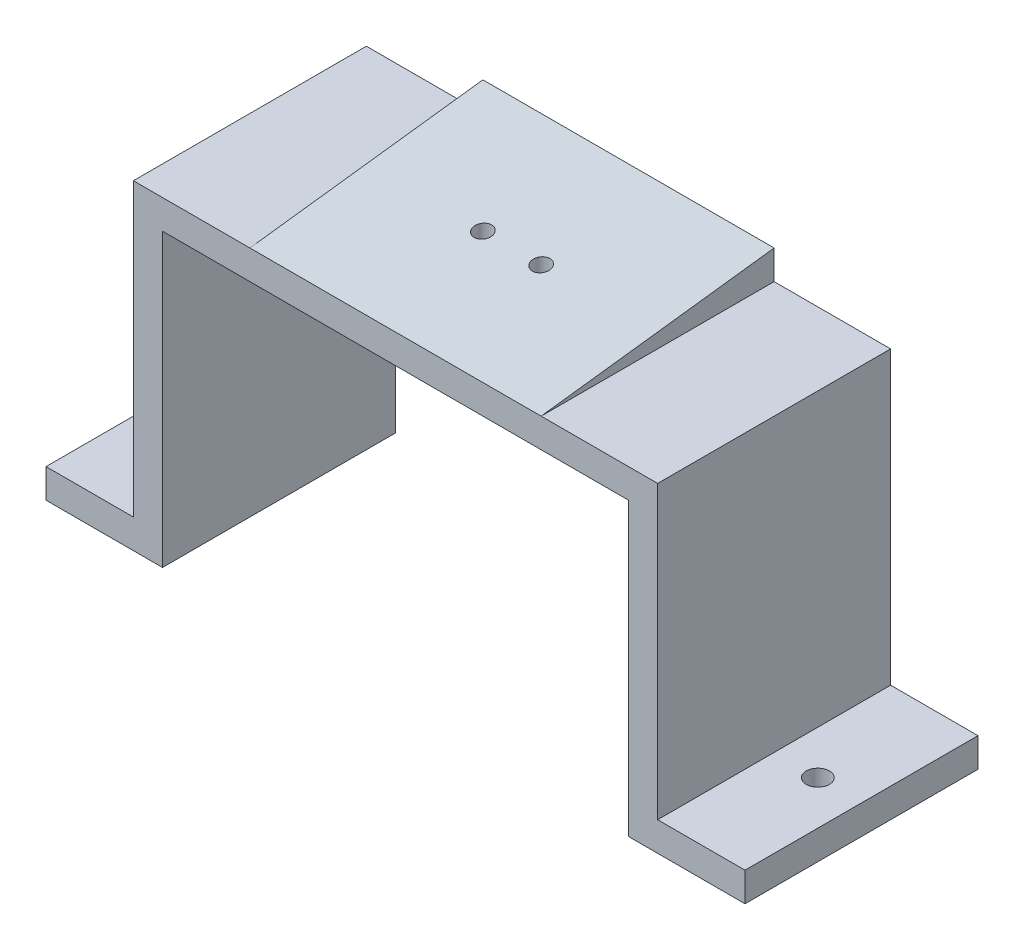
SolidWorks part; units mm, degrees
ref_plane "Front Plane" through (0, 0, 0) normal (0, 0, 1) x (1, 0, 0)
ref_plane "Top Plane" through (0, 0, 0) normal (0, 1, 0) x (1, 0, 0)
ref_plane "Right Plane" through (0, 0, 0) normal (1, 0, 0) x (0, 0, -1)
sketch "Sketch1" plane through (0, 0, 0) normal (0, 1, 0) x (1, 0, 0)
  line L0 (0, 20) -> (0, -20) construction
  line L1 (-25, 20) -> (25, 20)
  line L2 (-25, 20) -> (-25, -20)
  line L3 (-25, -20) -> (25, -20)
  line L4 (25, 20) -> (25, -20)
  line L5 (-25, 20) -> (25, -20) construction
  line L6 (-25, -20) -> (25, 20) construction
  line L7 (-25, 0) -> (25, 0) construction
  circle A0 centre (5, 0) radius 1.5
  circle A1 centre (-5, 0) radius 1.5
  point P0 (0, 0)
  dimension "D3" = 3
  dimension "D1" = 50
  dimension "D2" = 40
  dimension "D4" = 5
extrude "Boss-Extrude1" add sketch "Sketch1" along normal blind 10
sketch "Sketch3" plane through (-25, 0, 0) normal (-1, 0, 0) x (0, 0, 1)
  line L5 (-20, 10) -> (20, 5)
  line L6 (20, 10) -> (20, 0) construction
  line L8 (20, 0) -> (-20, 5)
  line L9 (-20, 10) -> (-20, 0) construction
  line L11 (-20, 10) -> (20, 10)
  line L12 (20, 10) -> (20, 5)
  line L13 (-20, 5) -> (-20, 0)
  line L14 (-20, 0) -> (20, 0)
extrude "Cut-Extrude2" cut sketch "Sketch3" against normal blind 50
sketch "Sketch4" plane through (-25, 0, 0) normal (-1, 0, 0) x (0, 0, 1)
  line L1 (20, 5) -> (-19.9968, 5)
  line L2 (20, 5) -> (20, 0)
  line L3 (20, 0) -> (-19.9968, 0)
  line L4 (-19.9968, 5) -> (-19.9968, 0)
extrude "Boss-Extrude2" add sketch "Sketch4" along normal blind 20
sketch "Sketch5" plane through (0, 0, 0) normal (0, -1, 0) x (1, 0, 0)
  line L0 (-45, -19.9968) -> (-25, -19.9968) construction
  line L1 (-45, 20) -> (-40, 20)
  line L2 (-45, 20) -> (-45, -19.9968)
  line L3 (-45, -19.9968) -> (-40, -19.9968)
  line L4 (-40, 20) -> (-40, -19.9968)
  line L5 (-40, -195.1488) -> (-40, -198.1488) construction
extrude "Boss-Extrude3" add sketch "Sketch5" along normal blind 50
sketch "Sketch6" plane through (-45, 0, 0) normal (-1, 0, 0) x (0, 0, 1)
  line L0 (20, -50) -> (20, 5) construction
  line L1 (-19.9968, -50) -> (20, -50)
  line L2 (-19.9968, -50) -> (-19.9968, -45)
  line L3 (-19.9968, -45) -> (20, -45)
  line L4 (20, -50) -> (20, -45)
  dimension "D1" = 5
extrude "Boss-Extrude4" add sketch "Sketch6" along normal blind 15
ref_plane "Plane1" through (0, 0, 0) normal (1, 0, 0) x (0, 0, -1)
sketch "Sketch8" plane through (-25, 0, 0) normal (1, 0, 0) x (0, 0, -1)
  line L2 (19.9968, 0) -> (-20, 0) construction
  line L3 (9.9968, 0) -> (9.9968, 3.7496)
  line L4 (-20, 0) -> (19.9968, 4.9996) construction
  line L6 (9.9968, 3.7496) -> (20, 5)
  line L7 (20, 5) -> (19.9968, 0)
  line L8 (19.9968, 0) -> (9.9968, 0)
sketch "Sketch9" plane through (0, -45, 0) normal (0, 1, 0) x (1, 0, 0)
  line L0 (-60, -0.0016) -> (-45, -0.0016) construction
  line L1 (-60, -20) -> (-60, 19.9968) construction
  line L2 (-45, -20) -> (-45, 19.9968) construction
  line L3 (-52.5, -20) -> (-52.5, 19.9968) construction
  line L4 (-60, -20) -> (-45, -20) construction
  line L5 (-60, 19.9968) -> (-45, 19.9968) construction
  circle A0 centre (-52.5, -0.0016) radius 2
  dimension "D1" = 4
extrude "Cut-Extrude6" cut sketch "Sketch9" against normal up to surface (5 mm away) up to face at (-50, -50, 0.0016)
mirror "Mirror3" about plane through (0, 0, 0) normal (1, 0, 0) of "Cut-Extrude6", "Boss-Extrude4", "Boss-Extrude3", "Boss-Extrude2"
